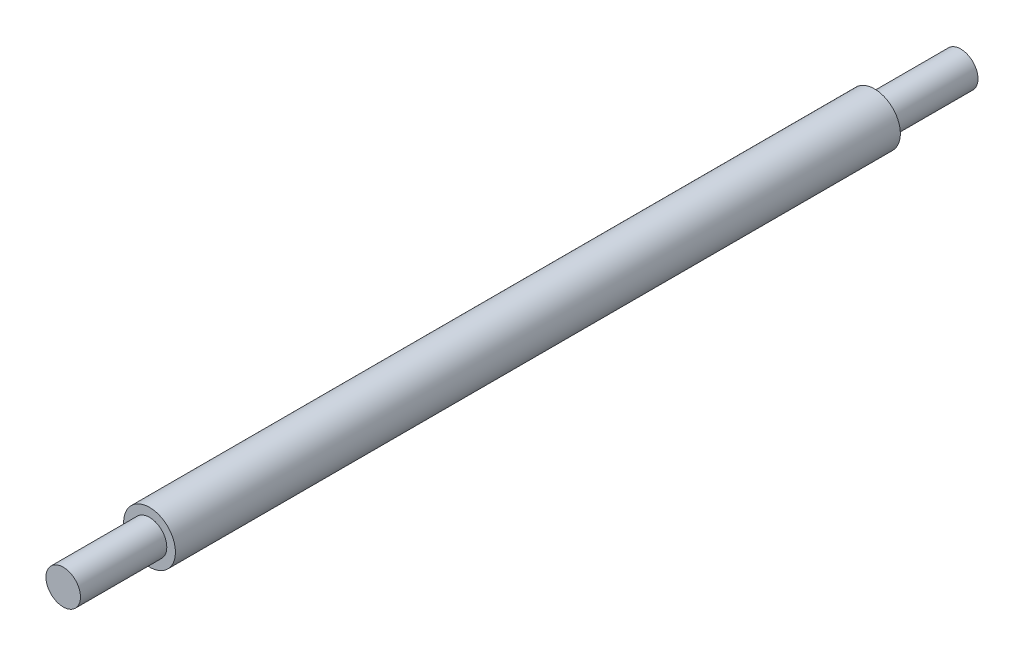
SolidWorks part; units mm, degrees
material "AISI 316 Annealed Stainless Steel Bar (SS)"
ref_plane "Front Plane" through (0, 0, 0) normal (0, 0, 1) x (1, 0, 0)
ref_plane "Top Plane" through (0, 0, 0) normal (0, 1, 0) x (1, 0, 0)
ref_plane "Right Plane" through (0, 0, 0) normal (1, 0, 0) x (0, 0, -1)
sketch "Sketch1" plane through (0, 0, 0) normal (0, 0, 1) x (1, 0, 0)
  circle A0 centre (0, 0) radius 3
  point P0 (0, 0)
  dimension "D1" = 6
extrude "Boss-Extrude1" add sketch "Sketch1" along normal mid plane 84
sketch "Sketch2" plane through (0, 0, 42) normal (0, 0, 1) x (1, 0, 0)
  circle A0 centre (0, 0) radius 2
  dimension "D1" = 4
extrude "Boss-Extrude2" add sketch "Sketch2" along normal blind 10
mirror "Mirror1" about plane through (0, 0, 0) normal (0, 0, 1) of "Boss-Extrude2"
